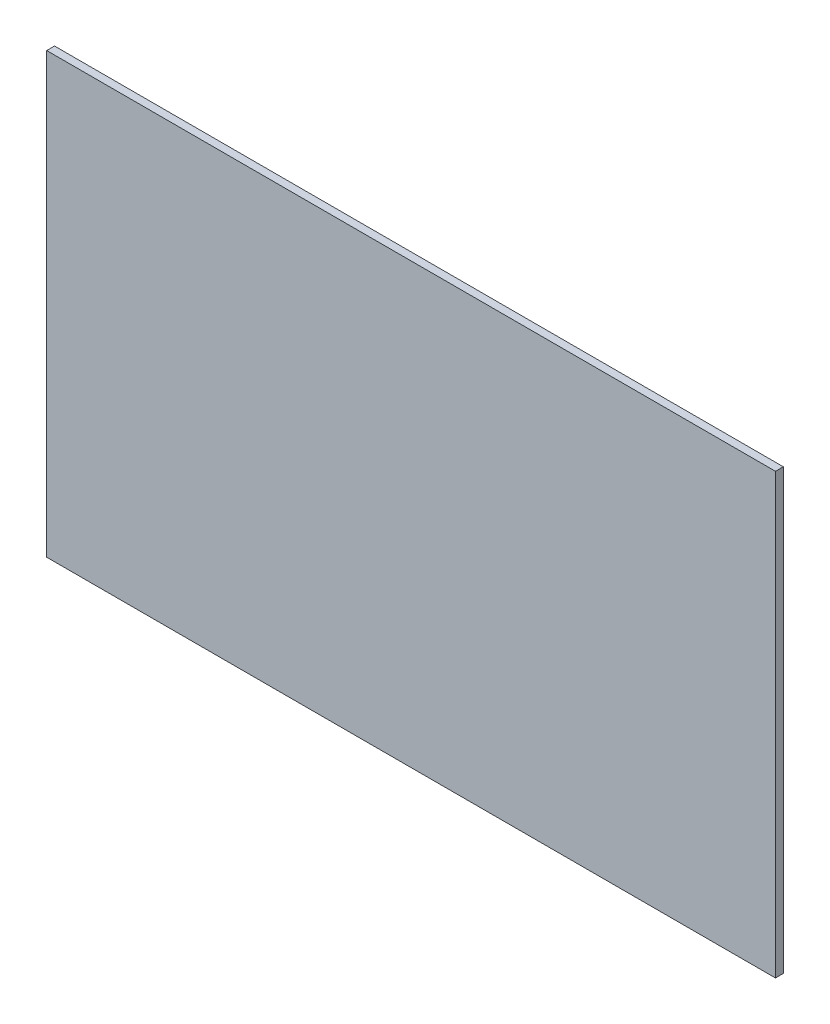
SolidWorks part; units mm, degrees
ref_plane "Front Plane" through (0, 0, 0) normal (0, 0, 1) x (1, 0, 0)
ref_plane "Top Plane" through (0, 0, 0) normal (0, 1, 0) x (1, 0, 0)
ref_plane "Right Plane" through (0, 0, 0) normal (1, 0, 0) x (0, 0, -1)
sketch "Sketch1" plane through (0, 0, 0) normal (0, 0, 1) x (1, 0, 0)
  line L1 (0, 0) -> (465, 0)
  line L2 (0, 0) -> (0, 280)
  line L3 (0, 280) -> (465, 280)
  line L4 (465, 0) -> (465, 280)
  dimension "D1" = 280
  dimension "D2" = 465
extrude "Boss-Extrude1" add sketch "Sketch1" along normal blind 5
